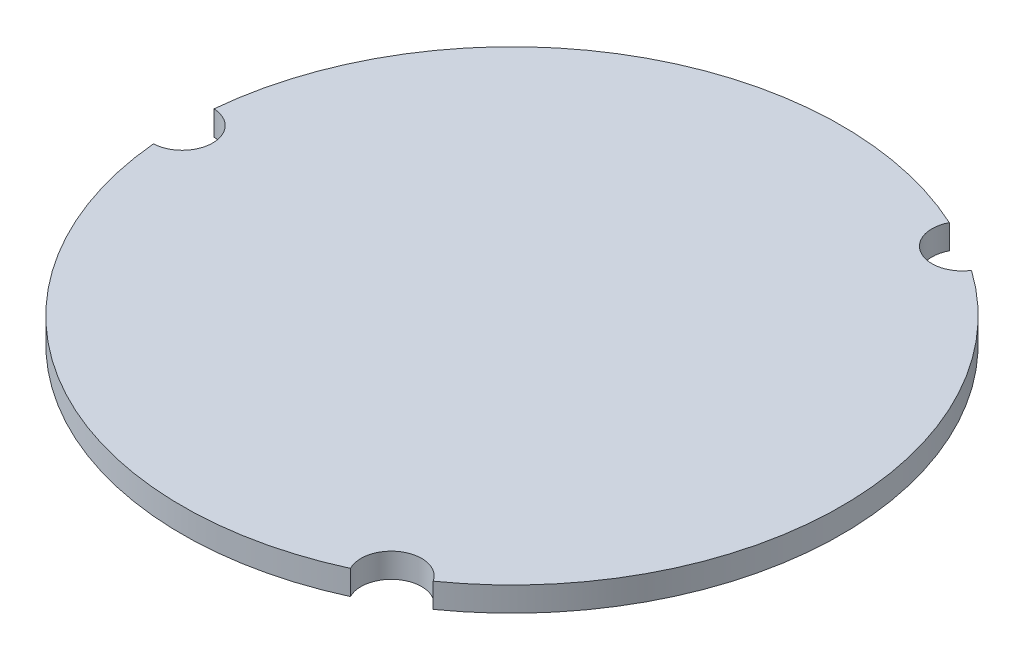
SolidWorks part; units mm, degrees
ref_plane "Plan de face" through (0, 0, 0) normal (0, 0, 1) x (1, 0, 0)
ref_plane "Plan de dessus" through (0, 0, 0) normal (0, 1, 0) x (1, 0, 0)
ref_plane "Plan de droite" through (0, 0, 0) normal (1, 0, 0) x (0, 0, -1)
sketch "Esquisse1" plane through (0, 0, 0) normal (0, 1, 0) x (1, 0, 0)
  line L0 (-33.7, 0) -> (33.7, 0) construction
  circle A0 centre (0, 0) radius 33.7
  arc A1 (-33.5574, 3.0967) -> (-33.5574, -3.0967) centre (-33.7, 0) cw
  arc A2 (19.4605, 27.5132) -> (14.0969, 30.6099) centre (16.85, 29.1851) cw
  arc A3 (14.0969, -30.6099) -> (19.4605, -27.5132) centre (16.85, -29.1851) cw
  point P16 (0, 0)
  dimension "D1" = 67.4
  dimension "D2" = 3.1
  dimension "D3" = 3
extrude "Boss.-Extru.1" add sketch "Esquisse1" along normal blind 2.5 contours L0 A1 A0 A3 | A1 L0 A0 A2
